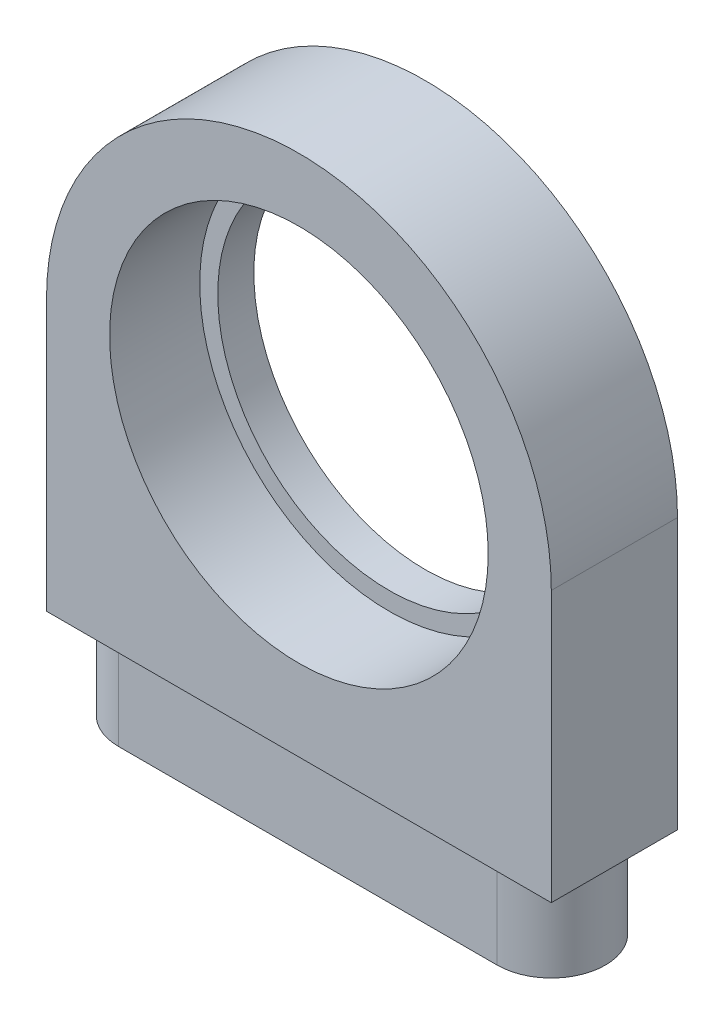
SolidWorks part; units mm, degrees
material "1060 Alloy"
ref_plane "Front Plane" through (0, 0, 0) normal (0, 0, 1) x (1, 0, 0)
ref_plane "Top Plane" through (0, 0, 0) normal (0, 1, 0) x (1, 0, 0)
ref_plane "Right Plane" through (0, 0, 0) normal (1, 0, 0) x (0, 0, -1)
sketch "Sketch1" plane through (0, 0, 0) normal (0, 1, 0) x (1, 0, 0)
  line L0 (-10.5, 0) -> (10.5, 0) construction
  line L1 (-44.2539, 0) -> (44.2539, 0) construction
  line L2 (-10.5, 3) -> (10.5, 3)
  line L3 (-10.5, -3) -> (10.5, -3)
  line L4 (0, -44.7868) -> (0, 44.7868) construction
  arc A0 (-10.5, 3) -> (-10.5, -3) centre (-10.5, 0) ccw
  arc A1 (10.5, -3) -> (10.5, 3) centre (10.5, 0) ccw
  point P5 (0, 0)
  dimension "D2" = 3
  dimension "D1" = 21
  dimension "D3" = 0
extrude "Boss-Extrude1" add sketch "Sketch1" against normal blind 5
sketch "Sketch2" plane through (0, 0, 0) normal (0, 1, 0) x (1, 0, 0)
  line L1 (-14, 3.5) -> (14, 3.5)
  line L2 (-14, 3.5) -> (-14, -3.5)
  line L3 (-14, -3.5) -> (14, -3.5)
  line L4 (14, 3.5) -> (14, -3.5)
  line L5 (-14, 3.5) -> (14, -3.5) construction
  line L6 (-14, -3.5) -> (14, 3.5) construction
  point P0 (0, 0)
  dimension "D1" = 28
  dimension "D2" = 7
extrude "Boss-Extrude2" add sketch "Sketch2" along normal blind 29
sketch "Sketch3" plane through (0, 0, 3.5) normal (0, 0, 1) x (1, 0, 0)
  line L0 (0, -44.7868) -> (0, 44.7868) construction
  line L1 (-14, 29) -> (-14, 0) construction
  line L2 (14, 29) -> (14, 0) construction
  line L3 (-14, 29) -> (14, 29) construction
  line L4 (-14, 15) -> (-14, 33.5127)
  line L5 (-14, 33.5127) -> (14, 33.5127)
  line L6 (14, 33.5127) -> (14, 15)
  arc A0 (-14, 15) -> (14, 15) centre (0, 15) cw
  dimension "D1" = 14
  dimension "D2" = 14
extrude "Cut-Extrude1" cut sketch "Sketch3" against normal blind 7
sketch "Sketch4" plane through (0, 0, 3.5) normal (0, 0, 1) x (1, 0, 0)
  circle A0 centre (0, 15) radius 10.5
  dimension "D1" = 21
extrude "Cut-Extrude2" cut sketch "Sketch4" against normal blind 5
sketch "Sketch5" plane through (0, 0, -1.5) normal (0, 0, 1) x (1, 0, 0)
  circle A0 centre (0, 15) radius 9.5
  dimension "D1" = 19
extrude "Cut-Extrude3" cut sketch "Sketch5" against normal blind 2
